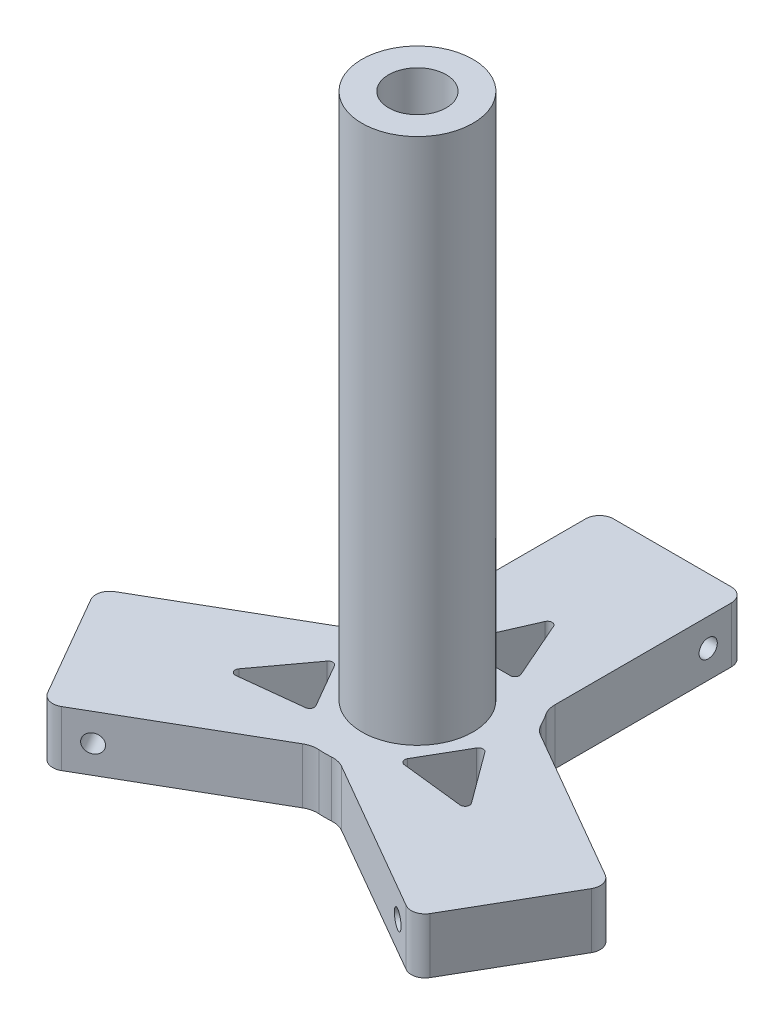
SolidWorks part; units mm, degrees
ref_plane "Front Plane" through (0, 0, 0) normal (0, 0, 1) x (1, 0, 0)
ref_plane "Top Plane" through (0, 0, 0) normal (0, 1, 0) x (1, 0, 0)
ref_plane "Right Plane" through (0, 0, 0) normal (1, 0, 0) x (0, 0, -1)
sketch "Sketch1" plane through (0, 0, 0) normal (0, 1, 0) x (1, 0, 0)
  line L0 (0, 35) -> (10, 35)
  line L1 (0, 35) -> (-10, 35)
  line L2 (0, 35) -> (0, 0) construction
  line L3 (0, 0) -> (-30.3109, -17.5) construction
  line L4 (0, 0) -> (30.3109, -17.5) construction
  line L5 (-10, 35) -> (-10, 7.8288)
  line L6 (10, 35) -> (10, 7.8288)
  line L7 (30.3109, -17.5) -> (35.3109, -8.8397)
  line L8 (30.3109, -17.5) -> (25.3109, -26.1603)
  line L9 (-30.3109, -17.5) -> (-35.3109, -8.8397)
  line L10 (-30.3109, -17.5) -> (-25.3109, -26.1603)
  line L11 (-35.3109, -8.8397) -> (-11.7799, 4.7459)
  line L12 (-25.3109, -26.1603) -> (-1.7799, -12.5747)
  line L13 (25.3109, -26.1603) -> (1.7799, -12.5747)
  line L14 (35.3109, -8.8397) -> (11.7749, 4.7582)
  circle A0 centre (0, 0) radius 35 construction
  arc A1 (-10, 7.8288) -> (-11.7799, 4.7459) centre (0, 0) ccw construction
  arc A2 (-10, 7.8288) -> (-11.7799, 4.7459) centre (0, 0) ccw
  arc A3 (11.7749, 4.7582) -> (10, 7.8288) centre (0, 0) ccw construction
  arc A4 (11.7749, 4.7582) -> (10, 7.8288) centre (0, 0) ccw
  arc A5 (-1.7799, -12.5747) -> (1.7799, -12.5747) centre (0, 0) ccw construction
  arc A6 (-1.7799, -12.5747) -> (1.7799, -12.5747) centre (0, 0) ccw
  dimension "D1" = 70
  dimension "D6" = 25.4
  dimension "D2" = 10
  dimension "D3" = 20
  dimension "D4" = 120
  dimension "D5" = 120
  dimension "D7" = 90
  dimension "D8" = 10
  dimension "D9" = 20
  dimension "D10" = 90
  dimension "D11" = 10
  dimension "D12" = 20
  dimension "D13" = 90
extrude "Boss-Extrude1" add sketch "Sketch1" along normal blind 7.62
hole_wizard "M3x0.5 Tapped Hole2" positions "Sketch4" profile "Sketch5" tap size "M3x0.5" standard "ANSI Metric" end condition through all
sketch "Sketch4" plane through (10, 0, 0) normal (1, 0, 0) x (0, 0, -1)
  line L0 (35, 7.62) -> (35, 0) construction
  point P0 (29.92, 3.81)
  point P5 (35, 3.81)
  dimension "D1" = 5.08
sketch "Sketch5" plane through (10, 3.81, -29.92) normal (0, 1, 0) x (0, 0, -1)
  line L0 (0, 0) -> (0, 45.3109)
  line L1 (0, 45.3109) -> (1.25, 45.3109)
  line L2 (1.25, 45.3109) -> (1.25, 0)
  line L5 (1.25, 0) -> (0, 0)
  line L11 (0, -6.35) -> (0, 107.95) construction
  dimension "Thru Tap Drill Dia." = 2.5
  dimension "Thru Tap Drill Depth" = 45.3109
cosmetic thread "Hole Thread2" parameters "D2"=3
hole_wizard "M3x0.5 Tapped Hole3" positions "Sketch6" profile "Sketch7" tap size "M3x0.5" standard "ANSI Metric" end condition through all
sketch "Sketch6" plane through (-5, 0, -8.6603) normal (-0.5, 0, -0.866) x (-0.866, 0, 0.5)
  line L0 (35, 7.62) -> (35, 0) construction
  point P0 (29.92, 3.81)
  point P5 (35, 3.81)
  dimension "D1" = 5.08
sketch "Sketch7" plane through (-30.9115, 3.81, 6.2997) normal (0, 1, 0) x (-0.866, 0, 0.5)
  line L0 (0, 0) -> (0, 50.3109)
  line L1 (0, 50.3109) -> (1.25, 50.3109)
  line L2 (1.25, 50.3109) -> (1.25, 0)
  line L5 (1.25, 0) -> (0, 0)
  line L11 (0, -6.35) -> (0, 107.95) construction
  dimension "Thru Tap Drill Dia." = 2.5
  dimension "Thru Tap Drill Depth" = 50.3109
cosmetic thread "Hole Thread3" parameters "D2"=3
hole_wizard "M3x0.5 Tapped Hole4" positions "Sketch8" profile "Sketch9" tap size "M3x0.5" standard "ANSI Metric" end condition through all
sketch "Sketch8" plane through (-5, 0, 8.6603) normal (-0.5, 0, 0.866) x (0.866, 0, 0.5)
  line L0 (35, 7.62) -> (35, 0) construction
  point P0 (29.92, 3.81)
  point P5 (35, 3.81)
  dimension "D1" = 5.08
sketch "Sketch9" plane through (20.9115, 3.81, 23.6203) normal (0, 1, 0) x (0.866, 0, 0.5)
  line L0 (0, 0) -> (0, 57.9663)
  line L1 (0, 57.9663) -> (1.25, 57.9663)
  line L2 (1.25, 57.9663) -> (1.25, 0)
  line L5 (1.25, 0) -> (0, 0)
  line L11 (0, -6.35) -> (0, 107.95) construction
  dimension "Thru Tap Drill Dia." = 2.5
  dimension "Thru Tap Drill Depth" = 57.9663
cosmetic thread "Hole Thread4" parameters "D2"=3
fillet "Fillet1" radius 3.175 6 edges at (-11.7799, 3.81, -4.7459) (-10, 3.81, -7.8288) (-1.7799, 3.81, 12.5747) (1.7799, 3.81, 12.5747) (11.7749, 3.81, -4.7582) (10, 3.81, -7.8288)
sketch "Sketch10" plane through (0, 7.62, 0) normal (0, 1, 0) x (1, 0, 0)
  circle A0 centre (0, 0) radius 7.62
  dimension "D1" = 15.24
extrude "Cut-Extrude1" cut sketch "Sketch10" against normal through all
sketch "Sketch11" plane through (0, 7.62, 0) normal (0, 1, 0) x (1, 0, 0)
  line L0 (0, 19.4327) -> (-4.445, 9.2727)
  line L1 (-4.445, 9.2727) -> (4.445, 9.2727)
  line L2 (4.445, 9.2727) -> (0, 19.4327)
  line L3 (10, 35) -> (-10, 35) construction
  point P2 (0, 9.2727)
  point P7 (0, 35)
  dimension "D1" = 8.89
  dimension "D2" = 10.16
extrude "Cut-Extrude2" cut sketch "Sketch11" against normal through all
fillet "Fillet2" radius 0.635 3 edges at (-4.445, 3.81, -9.2727) (4.445, 3.81, -9.2727) (0, 3.81, -19.4327)
pattern_circular "CirPattern1" count 2 over 120 about axis through (0, 0, 0) along (0, 1, 0) of "Fillet2", "Cut-Extrude2"
pattern_circular "CirPattern5" count 2 over 240 about axis through (0, 0, 0) along (0, 1, 0) of "Cut-Extrude2", "Fillet2"
fillet "Fillet3" radius 1.905 6 edges at (25.3109, 3.81, 26.1603) (35.3109, 3.81, 8.8397) (10, 3.81, -35) (-10, 3.81, -35) (-35.3109, 3.81, 8.8397) (-25.3109, 3.81, 26.1603)
sketch "Sketch12" plane through (0, 0, 0) normal (0, -1, 0) x (1, 0, 0)
  circle A0 centre (0, 0) radius 7.62
extrude "Boss-Extrude3" add sketch "Sketch12" against normal blind 80 separate body
sketch "Sketch14" plane through (0, 0, 0) normal (0, -1, 0) x (1, 0, 0)
  circle A0 centre (0, 0) radius 3.95
  dimension "D1" = 7.9
extrude "Cut-Extrude3" cut sketch "Sketch14" against normal through all
